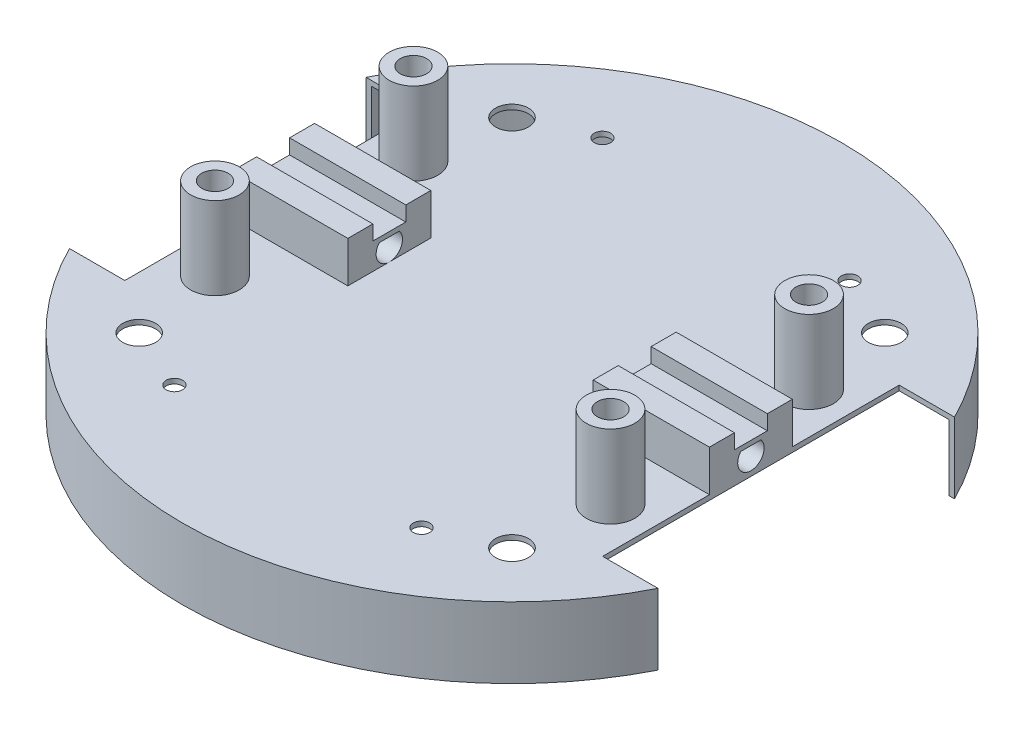
SolidWorks part; units mm, degrees
ref_plane "前视基准面" through (0, 0, 0) normal (0, 0, 1) x (1, 0, 0)
ref_plane "上视基准面" through (0, 0, 0) normal (0, 1, 0) x (1, 0, 0)
ref_plane "右视基准面" through (0, 0, 0) normal (1, 0, 0) x (0, 0, -1)
sketch "草图1" plane through (0, 0, 0) normal (0, 1, 0) x (1, 0, 0)
  line L0 (0, 0) -> (50000, 0) construction
  line L1 (0, 0) -> (0, 50000) construction
  circle A0 centre (0, 0) radius 200
extrude "凸台-拉伸1" add sketch "草图1" along normal blind 3 contours A0
sketch "草图2" plane through (0, 0, 0) normal (0, -1, 0) x (1, 0, 0)
  circle A0 centre (0, 0) radius 200
  circle A1 centre (0, 0) radius 197
extrude "凸台-拉伸2" add sketch "草图2" along normal blind 40
sketch "草图3" plane through (0, 3, 0) normal (0, 1, 0) x (1, 0, 0)
  line L0 (0, 0) -> (50000, 0) construction
  line L1 (0, 0) -> (0, 50000) construction
  line L2 (0, 0) -> (141.4214, 141.4214) construction
  line L3 (-178.6057, 90) -> (178.6057, 90)
  line L4 (-178.6057, -90) -> (178.6057, -90)
  line L5 (-145, 90) -> (-145, -90) construction
  line L6 (-145, 90) -> (-145, -90)
  line L7 (145, 90) -> (145, -90)
  circle A0 centre (0, 0) radius 200 construction
  circle A1 centre (113.1371, 113.1371) radius 10
  circle A2 centre (-113.1371, 113.1371) radius 10
  circle A3 centre (-113.1371, -113.1371) radius 10
  circle A4 centre (113.1371, -113.1371) radius 10
  circle A5 centre (-75, 129.9038) radius 5
  circle A6 centre (75, 129.9038) radius 5
  circle A7 centre (-75, -129.9038) radius 5
  circle A8 centre (75, -129.9038) radius 5
  circle M7 centre (0, 0) radius 200
  dimension "D1" = 160
  dimension "D3" = 145
  dimension "D4" = 150
  dimension "D2" = 180
  dimension "D5" = 150
extrude "切除-拉伸2" cut sketch "草图3" against normal through all contours L3 L7 L4 M7 | L6 L3 L4 M7 | A2 | A3 | A5 | A1 | A6 | A7 | A4 | A8
sketch "草图4" plane through (0, 3, 0) normal (0, 1, 0) x (1, 0, 0)
  line L0 (-145, 0) -> (49855, 0) construction
  line L1 (-145, 90) -> (-145, -90) construction
  line L2 (0, 0) -> (0, 50000) construction
  line L3 (145, 10) -> (74.4613, 10)
  line L4 (-145, -25.1788) -> (-74.4613, -25.1788)
  line L5 (-145, -25.1788) -> (-145, 25.1788)
  line L6 (-145, 25.1788) -> (-74.4613, 25.1788)
  line L7 (-74.4613, -25.1788) -> (-74.4613, 25.1788)
  line L8 (-145, -10) -> (-74.4613, -10)
  line L9 (-145, -10) -> (-145, 10)
  line L10 (-145, 10) -> (-74.4613, 10)
  line L11 (-74.4613, -10) -> (-74.4613, 10)
  line L12 (74.4613, -10) -> (74.4613, 10)
  line L13 (145, -10) -> (74.4613, -10)
  line L14 (145, -10) -> (145, 10)
  line L15 (145, 25.1788) -> (74.4613, 25.1788)
  line L16 (74.4613, -25.1788) -> (74.4613, 25.1788)
  line L17 (145, -25.1788) -> (74.4613, -25.1788)
  line L18 (145, -25.1788) -> (145, 25.1788)
  point P4 (-145, 0)
  line M6 (145, -90) -> (145, 90)
  line M10 (-145, 90) -> (-145, -90)
  dimension "D1" = 20
extrude "凸台-拉伸4" add sketch "草图4" along normal blind 25 contours L10 L7 L6 M10 | L8 L5 L4 L7 | L16 L3 L15 M6 | L17 L13 L16 M6
sketch "草图7" plane through (0, 3, 0) normal (0, 1, 0) x (1, 0, 0)
  line L0 (-74.4613, 10) -> (-74.4613, -10)
  line L1 (-74.4613, -10) -> (-145, -10)
  line L2 (-145, -10) -> (-145, 10)
  line L3 (-145, 10) -> (-74.4613, 10)
  line L4 (0, 0) -> (0, 50000) construction
  line L5 (0, 0) -> (50000, 0) construction
  line L6 (145, -10) -> (145, 10)
  line L7 (74.4613, -10) -> (145, -10)
  line L8 (74.4613, 10) -> (74.4613, -10)
  line L9 (145, 10) -> (74.4613, 10)
extrude "凸台-拉伸5" add sketch "草图7" along normal blind 16 contours L3 L0 L1 L2 | L6 L9 L8 L7
sketch "草图8" plane through (-145, 0, 0) normal (-1, 0, 0) x (0, 0, 1)
  line L0 (-25.1788, 3) -> (25.1788, 3)
  line L1 (0, 19) -> (0, 3)
  line L2 (-90, 0) -> (90, 0) construction
  line L3 (10, 19) -> (-10, 19) construction
  line L4 (-10, 19) -> (-10, 3)
  line L5 (10, 19) -> (10, 3)
  line L6 (-10, 19) -> (10, 19)
  line L7 (-6.0795, 16.2) -> (6.0795, 16.2)
  circle A0 centre (0, 11) radius 8
  dimension "D1" = 13.2
extrude "切除-拉伸5" cut sketch "草图8" against normal through all contours L1 A0 L7 | L7 A0 L1
sketch "草图10" plane through (0, 3, 0) normal (0, 1, 0) x (1, 0, 0)
  line L0 (0, 0) -> (50000, 0) construction
  line L1 (0, 0) -> (0, 50000) construction
  line L2 (-145, 90) -> (-145, 25.1788) construction
  line L3 (-135, 75) -> (-105, 75)
  line L4 (-135, 75) -> (-135, 45)
  line L5 (-135, 45) -> (-105, 45)
  line L6 (-105, 75) -> (-105, 45)
  line L7 (-135, -45) -> (-105, -45)
  line L8 (-105, -75) -> (-105, -45)
  line L9 (-135, -75) -> (-105, -75)
  line L10 (-135, -75) -> (-135, -45)
  line L11 (135, -75) -> (135, -45)
  line L12 (135, -75) -> (105, -75)
  line L13 (105, -75) -> (105, -45)
  line L14 (135, -45) -> (105, -45)
  line L15 (135, 45) -> (105, 45)
  line L16 (105, 75) -> (105, 45)
  line L17 (135, 75) -> (105, 75)
  line L18 (135, 75) -> (135, 45)
  circle A0 centre (-120.0482, 60.2463) radius 14.7537
  circle A1 centre (-120.0482, 60.2463) radius 8
  circle A2 centre (-120.0482, -60.2463) radius 14.7537
  circle A3 centre (-120.0482, -60.2463) radius 8
  circle A4 centre (120.0482, -60.2463) radius 8
  circle A5 centre (120.0482, -60.2463) radius 14.7537
  circle A6 centre (120.0482, 60.2463) radius 14.7537
  circle A7 centre (120.0482, 60.2463) radius 8
  dimension "D1" = 45
  dimension "D2" = 10
extrude "凸台-拉伸8" add sketch "草图10" along normal blind 50 contours A0 A1 | A2 A3 | A5 A4 | A6 A7
sketch "草图12" plane through (0, 3, 0) normal (0, 1, 0) x (1, 0, 0)
  circle A0 centre (-120.0482, 60.2463) radius 8
  circle A1 centre (-120.0482, -60.2463) radius 8
  circle A2 centre (120.0482, -60.2463) radius 8
  circle A3 centre (120.0482, 60.2463) radius 8
extrude "切除-拉伸8" cut sketch "草图12" against normal blind 50 contours A0 | A1 | A2 | A3
